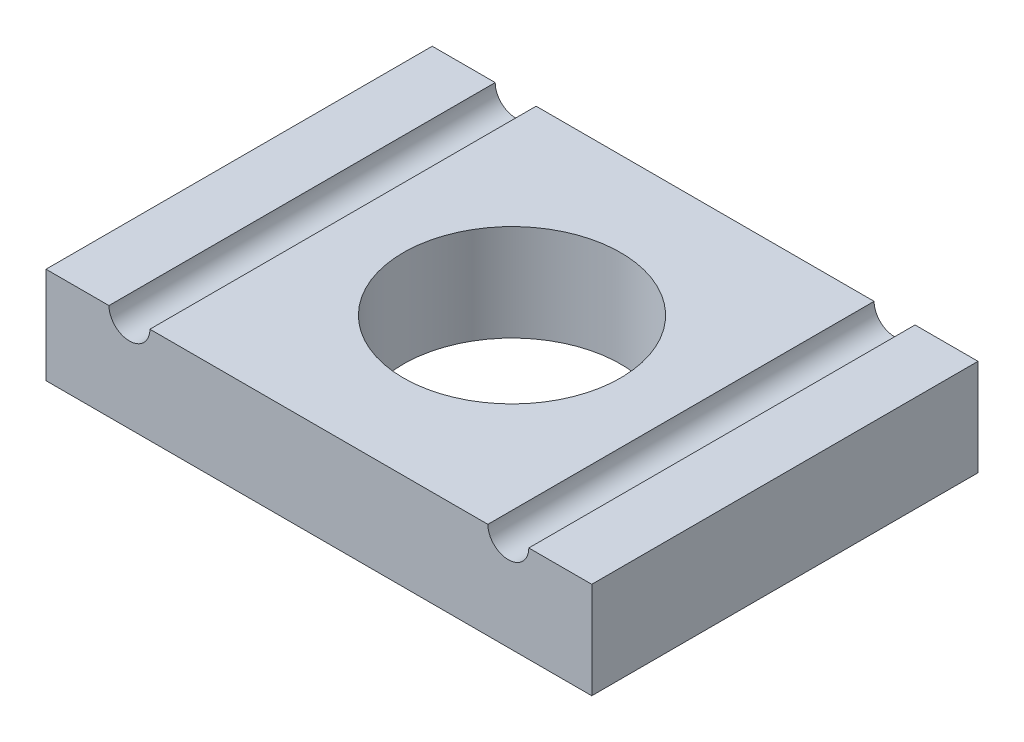
SolidWorks part; units mm, degrees
ref_plane "Front Plane" through (0, 0, 0) normal (0, 0, 1) x (1, 0, 0)
ref_plane "Top Plane" through (0, 0, 0) normal (0, 1, 0) x (1, 0, 0)
ref_plane "Right Plane" through (0, 0, 0) normal (1, 0, 0) x (0, 0, -1)
sketch "Sketch1" plane through (0, 0, 0) normal (0, 1, 0) x (1, 0, 0)
  line L1 (-17.9451, 12.7) -> (17.9451, 12.7)
  line L2 (-17.9451, 12.7) -> (-17.9451, -12.7)
  line L3 (-17.9451, -12.7) -> (17.9451, -12.7)
  line L4 (17.9451, 12.7) -> (17.9451, -12.7)
  circle A0 centre (0, 0) radius 7.1438
  dimension "D1" = 14.2875
  dimension "D2" = 35.8902
  dimension "D3" = 17.9451
  dimension "D4" = 25.4
  dimension "D5" = 12.7
extrude "Boss-Extrude1" add sketch "Sketch1" along normal blind 6.35
sketch "Sketch2" plane through (0, 0, 12.7) normal (0, 0, 1) x (1, 0, 0)
  line L0 (-17.9451, 6.35) -> (17.9451, 6.35) construction
  line L1 (-17.9451, 6.35) -> (-17.9451, 0) construction
  line L2 (17.9451, 6.35) -> (17.9451, 0) construction
  circle A0 centre (-12.4587, 6.35) radius 1.3462
  circle A1 centre (12.4587, 6.35) radius 1.3462
  dimension "D1" = 2.6924
  dimension "D2" = 2.6924
  dimension "D3" = 5.4864
  dimension "D4" = 5.4864
extrude "Cut-Extrude1" cut sketch "Sketch2" against normal through all
